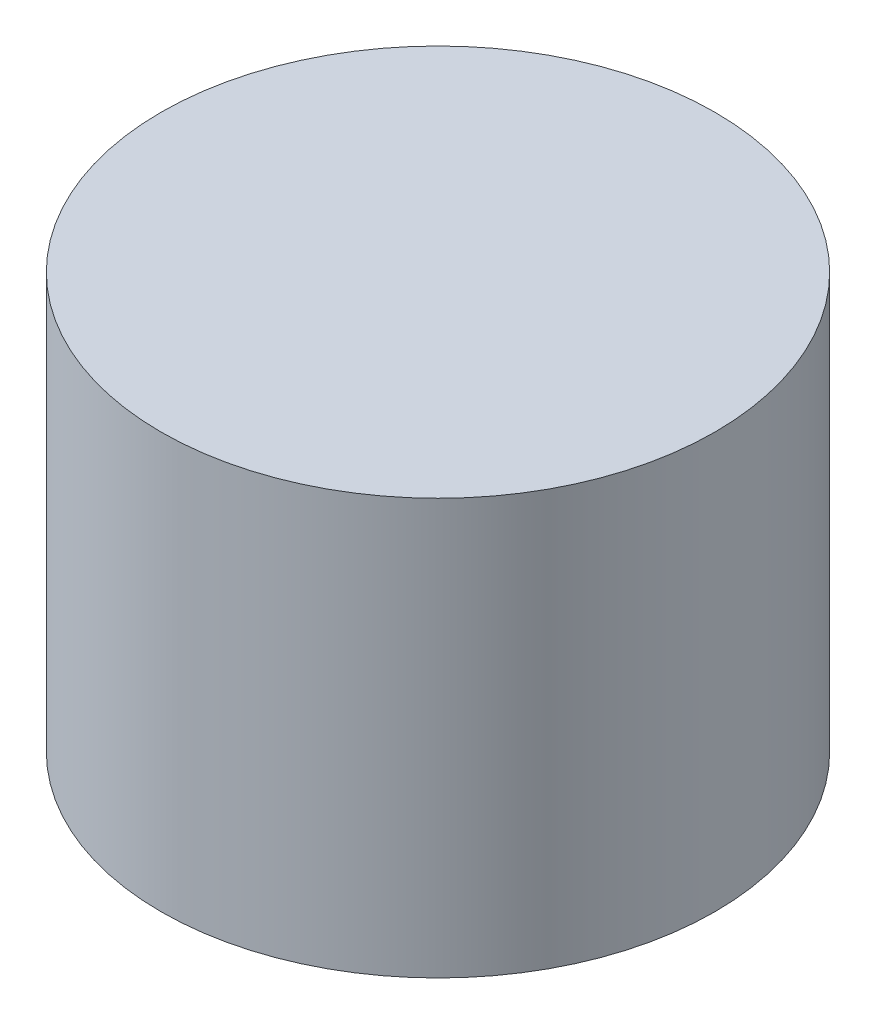
SolidWorks part; units mm, degrees
ref_plane "Front Plane" through (0, 0, 0) normal (0, 0, 1) x (1, 0, 0)
ref_plane "Top Plane" through (0, 0, 0) normal (0, 1, 0) x (1, 0, 0)
ref_plane "Right Plane" through (0, 0, 0) normal (1, 0, 0) x (0, 0, -1)
sketch "Sketch1" plane through (0, 0, 0) normal (0, 1, 0) x (1, 0, 0)
  circle A0 centre (0, 0) radius 25.4
  dimension "D1" = 50.8
extrude "Boss-Extrude1" add sketch "Sketch1" along normal blind 38.1
